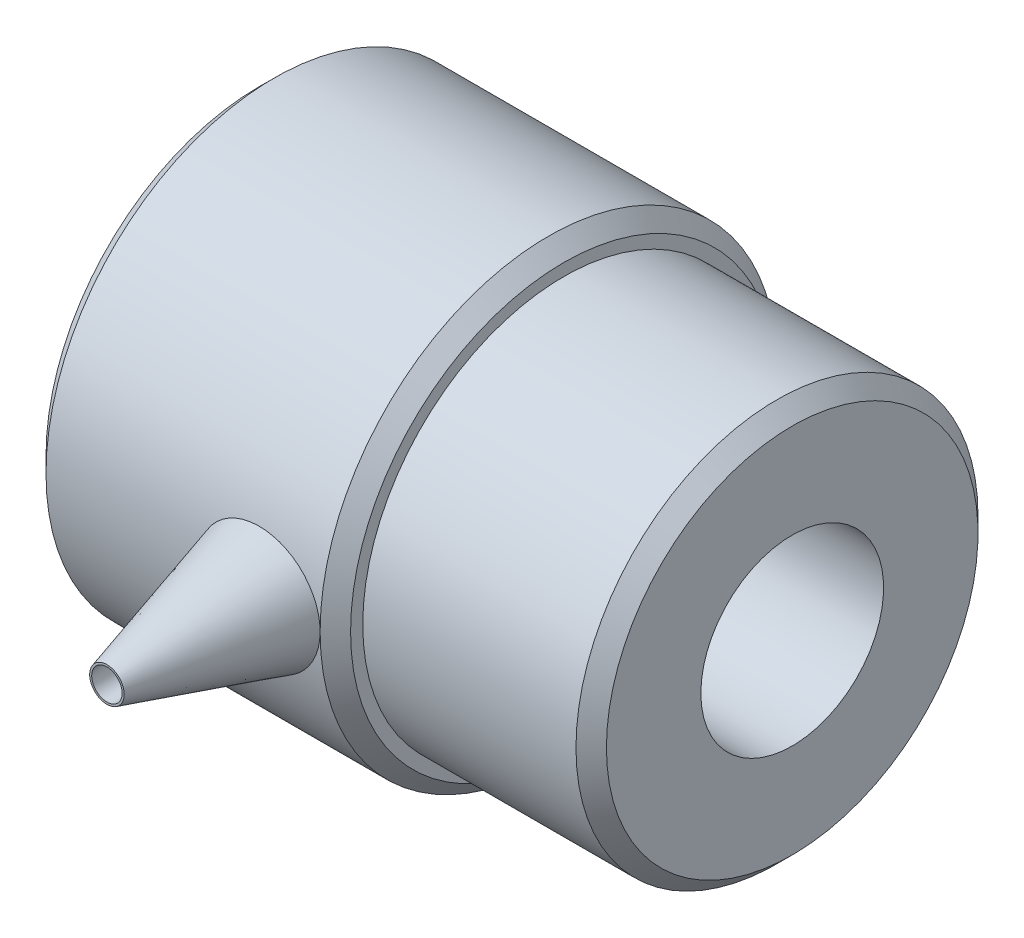
SolidWorks part; units mm, degrees
ref_plane "Plan de face" through (0, 0, 0) normal (0, 0, 1) x (1, 0, 0)
ref_plane "Plan de dessus" through (0, 0, 0) normal (0, 1, 0) x (1, 0, 0)
ref_plane "Plan de droite" through (0, 0, 0) normal (1, 0, 0) x (0, 0, -1)
sketch "Sketch1" plane through (0, 0, 0) normal (0, 0, 1) x (1, 0, 0)
  line L0 (0, 6) -> (0, 13.2)
  line L1 (0, 13.2) -> (-15, 13.2)
  line L2 (-15, 13.2) -> (-15, 15)
  line L3 (-15, 15) -> (-35, 15)
  line L4 (-35, 15) -> (-35, 11)
  line L6 (-35, 11) -> (-33, 11)
  line L7 (-33, 11) -> (-33, 10)
  line L8 (-33, 10) -> (-17.1197, 10)
  line L9 (-17.1197, 10) -> (-17.1197, 11)
  line L10 (-17.1197, 11) -> (-15.1197, 11)
  line L11 (-15.1197, 11) -> (-15.1197, 6)
  line L12 (-15.1197, 6) -> (0, 6)
  line L13 (-35, 0) -> (15.9149, 0) construction
  dimension "D2" = 20
  dimension "15" = 15
  dimension "D8" = 2
  dimension "D9" = 2
revolve "Revolve1" add sketch "Sketch1" angle 360 about L13
chamfer "Chamfer1" distance 0.5 angle 45 1 edges at (-33, 0, 10)
chamfer "Chamfer2" distance 0.5 angle 45 1 edges at (-15.1197, 0, 6)
chamfer "Chamfer3" distance 1 angle 45 3 edges at (-35, 0, 15) (-15, 0, 15) (0, 0, 13.2)
ref_plane "Plane1" through (0, 0, 15) normal (0, 0, 1) x (1, 0, 0)
sketch "Sketch2" plane through (0, 0, 15) normal (0, 0, 1) x (1, 0, 0)
  line L0 (-35, 14) -> (-35, -14) construction
  circle A0 centre (-20, 0) radius 2.5
  point P0 (-20, 0)
  dimension "D2" = 5
  dimension "D1" = 15
extrude "Extrude1" cut sketch "Sketch2" against normal blind 10
sketch "Sketch3" plane through (0, 0, 15) normal (0, 0, 1) x (1, 0, 0)
  circle A0 centre (-20, 0) radius 4
  dimension "D1" = 8
extrude "Extrude2" add sketch "Sketch3" along normal blind 10 draft 16 separate body
sketch "Sketch4" plane through (0, 0, 15) normal (0, 0, 1) x (1, 0, 0)
  circle A0 centre (-20, 0) radius 1
  dimension "D1" = 2
extrude "Extrude3" cut sketch "Sketch4" along normal blind 20
